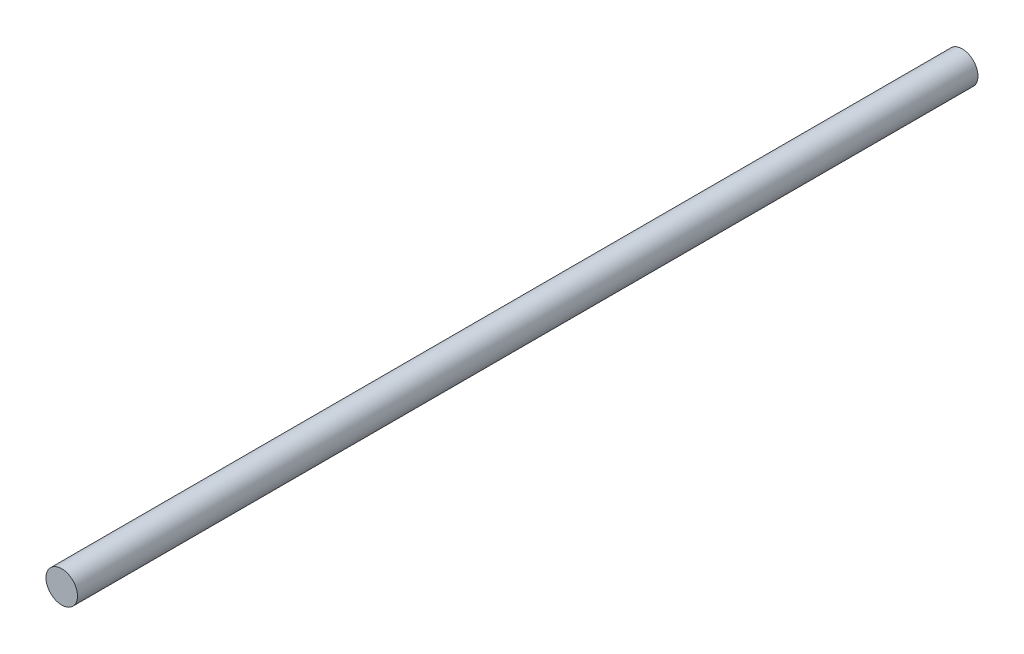
SolidWorks part; units mm, degrees
ref_plane "Front Plane" through (0, 0, 0) normal (0, 0, 1) x (1, 0, 0)
ref_plane "Top Plane" through (0, 0, 0) normal (0, 1, 0) x (1, 0, 0)
ref_plane "Right Plane" through (0, 0, 0) normal (1, 0, 0) x (0, 0, -1)
sketch "Sketch1" plane through (0, 0, 0) normal (0, 0, 1) x (1, 0, 0)
  line L0 (-55, 0) -> (55, 0) construction
  line L1 (0, -55) -> (0, 55) construction
  circle A0 centre (-20, 0) radius 7
  dimension "D1" = 14
  dimension "D2" = 20
extrude "Boss-Extrude1" add sketch "Sketch1" along normal blind 400
